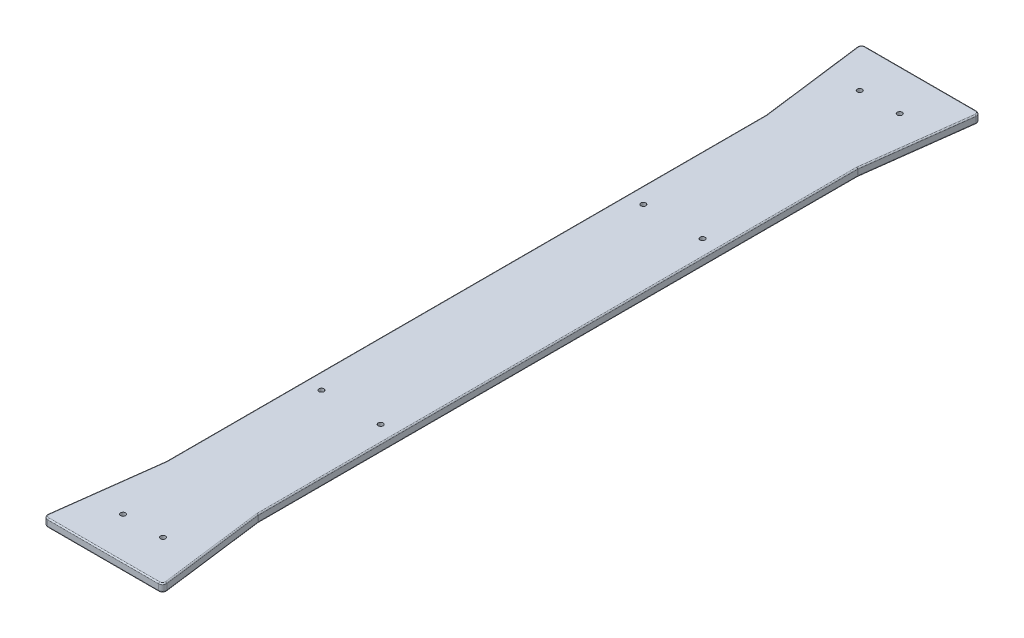
SolidWorks part; units mm, degrees
ref_plane "Front Plane" through (0, 0, 0) normal (0, 0, 1) x (1, 0, 0)
ref_plane "Top Plane" through (0, 0, 0) normal (0, 1, 0) x (1, 0, 0)
ref_plane "Right Plane" through (0, 0, 0) normal (1, 0, 0) x (0, 0, -1)
sketch "Sketch1" plane through (0, 0, 0) normal (0, 1, 0) x (1, 0, 0)
  line L0 (0, -259.782) -> (0, 259.782) construction
  line L2 (-29.21, -190.5) -> (-29.21, 190.5)
  line L4 (29.21, -190.5) -> (29.21, 190.5)
  line L5 (-29.21, -190.5) -> (29.21, 190.5) construction
  line L6 (-29.21, 190.5) -> (29.21, -190.5) construction
  line L7 (-29.21, 0) -> (29.21, 0) construction
  line L22 (-29.21, 190.5) -> (-38.1, 259.782)
  line L23 (-38.1, 259.782) -> (38.1, 259.782)
  line L24 (38.1, 259.782) -> (29.21, 190.5)
  line L25 (38.1, -259.782) -> (29.21, -190.5)
  line L26 (-38.1, -259.782) -> (38.1, -259.782)
  line L27 (-29.21, -190.5) -> (-38.1, -259.782)
  circle A0 centre (-18.796, 102.235) radius 1.5875
  circle A1 centre (18.796, 102.235) radius 1.5875
  circle A2 centre (18.796, -102.235) radius 1.5875
  circle A3 centre (-18.796, -102.235) radius 1.5875
  point P0 (0, 0)
  point P13 (0, 0)
  point P16 (0, 0)
  point P26 (0, 259.782)
  dimension "D6" = 3.175
  dimension "D1" = 58.42
  dimension "D2" = 381
  dimension "D3" = 37.592
  dimension "D4" = 204.47
  dimension "D5" = 37.592
  dimension "D7" = 76.2
  dimension "D8" = 69.85
extrude "Boss-Extrude1" add sketch "Sketch1" along normal blind 5.08
fillet "Fillet1" radius 2.54 7 edges at (-38.1, 2.54, -259.782) (-29.21, 2.54, 190.5) (-38.1, 2.54, 259.782) (38.1, 2.54, 259.782) (29.21, 2.54, 190.5) (29.21, 2.54, -190.5) (38.1, 2.54, -259.782)
fillet "Fillet2" radius 0.762 30 edges at (-33.4713, 5.08, -223.7093) (-37.1202, 5.08, -258.9198) (0, 5.08, -259.782) (29.21, 5.08, 0) (-29.21, 5.08, -0.0811) (37.1202, 5.08, -258.9198) (33.4816, 5.08, -223.7898) (29.2152, 5.08, -190.4997) (29.2152, 5.08, 190.4997) (33.4816, 5.08, 223.7898) (37.1202, 5.08, 258.9198) (0, 5.08, 259.782) (-37.1202, 5.08, 258.9198) (-33.4816, 5.08, 223.7898) (-29.2152, 5.08, 190.4997) (-29.21, 0, -0.0811) (-29.2152, 0, 190.4997) (-33.4816, 0, 223.7898) (-37.1202, 0, 258.9198) (0, 0, 259.782) (37.1202, 0, 258.9198) (33.4816, 0, 223.7898) (29.2152, 0, 190.4997) (-33.4713, 0, -223.7093) (-37.1202, 0, -258.9198) (0, 0, -259.782) (37.1202, 0, -258.9198) (33.4816, 0, -223.7898) (29.2152, 0, -190.4997) (29.21, 0, 0)
sketch "Sketch2" plane through (0, 5.08, 0) normal (0, 1, 0) x (1, 0, 0)
  line L0 (0, 259.02) -> (0, -259.02) construction
  line L1 (35.2133, 259.02) -> (-35.2133, 259.02) construction
  line L2 (-35.2133, -259.02) -> (35.2133, -259.02) construction
  line L3 (-28.448, 0.1055) -> (28.448, 0) construction
  line L4 (-28.448, 190.5487) -> (-28.448, -190.3377) construction
  line L5 (28.448, -190.3377) -> (28.448, 190.3377) construction
  circle A0 centre (-12.7, 233.62) radius 1.5875
  circle A1 centre (12.7, 233.62) radius 1.5875
  circle A2 centre (11.8338, -233.56) radius 1.5875
  circle A3 centre (-13.566, -233.4658) radius 1.5875
  dimension "D2" = 3.175
  dimension "D1" = 25.4
  dimension "D3" = 25.4
extrude "Cut-Extrude1" cut sketch "Sketch2" against normal through all
